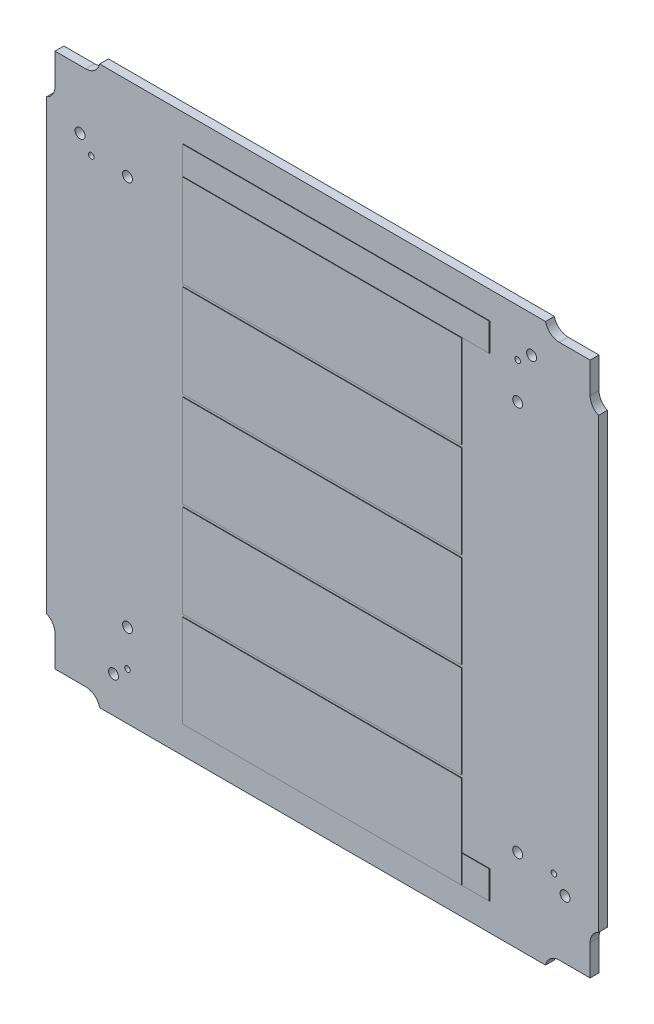
SolidWorks part; units mm, degrees
ref_plane "Front Plane" through (0, 0, 0) normal (0, 0, 1) x (1, 0, 0)
ref_plane "Top Plane" through (0, 0, 0) normal (0, 1, 0) x (1, 0, 0)
ref_plane "Right Plane" through (0, 0, 0) normal (1, 0, 0) x (0, 0, -1)
ref_plane "Plane1" through (0, 0, 1.5875) normal (0, 0, 1) x (1, 0, 0)
sketch "Sketch1" plane through (0, 0, 1.5875) normal (0, 0, 1) x (1, 0, 0)
  line L0 (49.5, 50) -> (-49.5, 50)
  line L1 (-49.5, 50) -> (-49.5, -50)
  line L2 (-49.5, -50) -> (49.5, -50)
  line L3 (49.5, -50) -> (49.5, 50)
  dimension "D1" = 99
  dimension "D2" = 100
extrude "Boss-Extrude1" add sketch "Sketch1" against normal blind 1.5875
sketch "Sketch2" plane through (0, 0, 0) normal (0, 0, -1) x (-1, 0, 0)
  line L0 (48, -42.4819) -> (48, -50)
  line L1 (48, -50) -> (49.5, -50)
  line L2 (49.5, -50) -> (49.5, -40.1646)
  line L3 (-49.5, -50) -> (-49.5, 50) construction
  line L4 (49.5, -50) -> (-49.5, -50) construction
  arc A0 (49.5, -40.1646) -> (48, -42.4819) centre (50.54, -42.4819) ccw
  dimension "D1" = 2.54
  dimension "D2" = 97.5
  dimension "D3" = 99
  dimension "D4" = 7.5181
extrude "Cut-Extrude1" cut sketch "Sketch2" against normal through all
sketch "Sketch3" plane through (0, 0, 0) normal (0, 0, -1) x (-1, 0, 0)
  line L0 (48, -48) -> (42.4819, -48)
  line L1 (40, -50) -> (48, -50)
  line L2 (48, -50) -> (48, -48)
  line L3 (49.5, 50) -> (49.5, -40.1646) construction
  arc A0 (42.4819, -48) -> (40, -50) centre (42.4819, -50.54) ccw
  dimension "D1" = 2.54
  dimension "D2" = 1.5
  dimension "D3" = 7.0181
  dimension "D4" = 9.5
extrude "Cut-Extrude2" cut sketch "Sketch3" against normal through all
sketch "Sketch4" plane through (0, 0, 0) normal (0, 0, -1) x (-1, 0, 0)
  line L0 (-42.4819, -48) -> (-49.5, -48)
  line L1 (-49.5, -48) -> (-49.5, -50)
  line L2 (-49.5, -50) -> (-40, -50)
  line L3 (48, -42.4819) -> (48, -48) construction
  line L4 (40, -50) -> (-49.5, -50) construction
  arc A0 (-40, -50) -> (-42.4819, -48) centre (-42.4819, -50.54) ccw
  dimension "D1" = 2.54
  dimension "D2" = 88
  dimension "D3" = 90.4819
  dimension "D4" = 97.5
  dimension "D5" = 2
extrude "Cut-Extrude3" cut sketch "Sketch4" against normal through all
sketch "Sketch5" plane through (0, 0, 0) normal (0, 0, -1) x (-1, 0, 0)
  line L0 (-48, -48) -> (-48, -42.4819)
  line L1 (-49.5, -40.1646) -> (-49.5, -48)
  line L2 (-49.5, -48) -> (-48, -48)
  line L3 (40, -50) -> (-40, -50) construction
  arc A0 (-48, -42.4819) -> (-49.5, -40.1646) centre (-50.54, -42.4819) ccw
  dimension "D1" = 2.54
  dimension "D2" = 96
  dimension "D3" = 97.5
  dimension "D4" = 2
  dimension "D5" = 7.5181
extrude "Cut-Extrude4" cut sketch "Sketch5" against normal through all
sketch "Sketch6" plane through (0, 0, 0) normal (0, 0, -1) x (-1, 0, 0)
  line L0 (-48, 42.4819) -> (-48, 50)
  line L1 (-48, 50) -> (-49.5, 50)
  line L2 (-49.5, 50) -> (-49.5, 40.1646)
  line L3 (-49.5, -40.1646) -> (-49.5, 50) construction
  line L4 (40, -50) -> (-40, -50) construction
  arc A0 (-49.5, 40.1646) -> (-48, 42.4819) centre (-50.54, 42.4819) ccw
  dimension "D1" = 2.54
  dimension "D2" = 1.5
  dimension "D3" = 90.1646
  dimension "D4" = 92.4819
  dimension "D5" = 100
extrude "Cut-Extrude5" cut sketch "Sketch6" against normal through all
sketch "Sketch7" plane through (0, 0, 0) normal (0, 0, -1) x (-1, 0, 0)
  line L0 (-48, 48) -> (-42.4819, 48)
  line L1 (-40, 50) -> (-48, 50)
  line L2 (-48, 50) -> (-48, 48)
  line L3 (-49.5, -40.1646) -> (-49.5, 40.1646) construction
  line L4 (-42.4819, -48) -> (-48, -48) construction
  arc A0 (-42.4819, 48) -> (-40, 50) centre (-42.4819, 50.54) ccw
  dimension "D1" = 2.54
  dimension "D2" = 1.5
  dimension "D3" = 7.0181
  dimension "D4" = 9.5
  dimension "D5" = 96
extrude "Cut-Extrude6" cut sketch "Sketch7" against normal through all
sketch "Sketch8" plane through (0, 0, 0) normal (0, 0, -1) x (-1, 0, 0)
  line L0 (42.4819, 48) -> (49.5, 48)
  line L1 (49.5, 48) -> (49.5, 50)
  line L2 (49.5, 50) -> (40, 50)
  line L3 (-49.5, -40.1646) -> (-49.5, 40.1646) construction
  line L4 (-40, 50) -> (49.5, 50) construction
  arc A0 (40, 50) -> (42.4819, 48) centre (42.4819, 50.54) ccw
  dimension "D1" = 2.54
  dimension "D2" = 89.5
  dimension "D3" = 91.9819
  dimension "D4" = 99
  dimension "D5" = 0.54
extrude "Cut-Extrude7" cut sketch "Sketch8" against normal through all
sketch "Sketch9" plane through (0, 0, 0) normal (0, 0, -1) x (-1, 0, 0)
  line L0 (48, 48) -> (48, 42.4819)
  line L1 (49.5, 40.1646) -> (49.5, 48)
  line L2 (49.5, 48) -> (48, 48)
  line L3 (-49.5, -40.1646) -> (-49.5, 40.1646) construction
  line L4 (-40, 50) -> (40, 50) construction
  arc A0 (48, 42.4819) -> (49.5, 40.1646) centre (50.54, 42.4819) ccw
  dimension "D1" = 2.54
  dimension "D2" = 97.5
  dimension "D3" = 99
  dimension "D4" = 2
  dimension "D5" = 7.5181
extrude "Cut-Extrude8" cut sketch "Sketch9" against normal through all
sketch "Sketch10" plane through (0, 0, 1.5875) normal (0, 0, 1) x (1, 0, 0)
  line L0 (25, 23.4) -> (-25, 23.4)
  line L1 (-25, 23.4) -> (-25, 40)
  line L2 (-25, 40) -> (25, 40)
  line L3 (25, 40) -> (25, 23.4)
  line L4 (-49.5, 40.1646) -> (-49.5, -40.1646) construction
  line L5 (-40, -50) -> (40, -50) construction
  dimension "D1" = 24.5
  dimension "D2" = 74.5
  dimension "D3" = 73.4
  dimension "D4" = 90
extrude "Boss-Extrude2" add sketch "Sketch10" along normal blind 0.1
sketch "Sketch11" plane through (0, 0, 1.5875) normal (0, 0, 1) x (1, 0, 0)
  line L0 (25, 6.3) -> (-25, 6.3)
  line L1 (-25, 6.3) -> (-25, 22.9)
  line L2 (-25, 22.9) -> (25, 22.9)
  line L3 (25, 22.9) -> (25, 6.3)
  line L4 (-49.5, 40.1646) -> (-49.5, -40.1646) construction
  line L5 (-40, -50) -> (40, -50) construction
  dimension "D1" = 24.5
  dimension "D2" = 74.5
  dimension "D3" = 56.3
  dimension "D4" = 72.9
extrude "Boss-Extrude3" add sketch "Sketch11" along normal blind 0.1
sketch "Sketch12" plane through (0, 0, 1.5875) normal (0, 0, 1) x (1, 0, 0)
  line L0 (25, -10.8) -> (-25, -10.8)
  line L1 (-25, -10.8) -> (-25, 5.8)
  line L2 (-25, 5.8) -> (25, 5.8)
  line L3 (25, 5.8) -> (25, -10.8)
  line L4 (-49.5, 40.1646) -> (-49.5, -40.1646) construction
  line L5 (-40, -50) -> (40, -50) construction
  dimension "D1" = 24.5
  dimension "D2" = 74.5
  dimension "D3" = 39.2
  dimension "D4" = 55.8
extrude "Boss-Extrude4" add sketch "Sketch12" along normal blind 0.1
sketch "Sketch13" plane through (0, 0, 1.5875) normal (0, 0, 1) x (1, 0, 0)
  line L0 (25, -27.9) -> (-25, -27.9)
  line L1 (-25, -27.9) -> (-25, -11.3)
  line L2 (-25, -11.3) -> (25, -11.3)
  line L3 (25, -11.3) -> (25, -27.9)
  line L4 (-49.5, 40.1646) -> (-49.5, -40.1646) construction
  line L5 (-40, -50) -> (40, -50) construction
  dimension "D1" = 24.5
  dimension "D2" = 74.5
  dimension "D3" = 22.1
  dimension "D4" = 38.7
extrude "Boss-Extrude5" add sketch "Sketch13" along normal blind 0.1
sketch "Sketch14" plane through (0, 0, 1.5875) normal (0, 0, 1) x (1, 0, 0)
  line L0 (25, -45) -> (-25, -45)
  line L1 (-25, -45) -> (-25, -28.4)
  line L2 (-25, -28.4) -> (25, -28.4)
  line L3 (25, -28.4) -> (25, -45)
  line L4 (-49.5, 40.1646) -> (-49.5, -40.1646) construction
  line L5 (-40, -50) -> (40, -50) construction
  dimension "D1" = 24.5
  dimension "D2" = 74.5
  dimension "D3" = 5
  dimension "D4" = 21.6
extrude "Boss-Extrude6" add sketch "Sketch14" along normal blind 0.1
sketch "Sketch15" plane through (0, 0, 1.5875) normal (0, 0, 1) x (1, 0, 0)
  line L0 (-25, 40.1) -> (-25, 45.1)
  line L1 (-25, 45.1) -> (30, 45.1)
  line L2 (30, 45.1) -> (30, 40.1)
  line L3 (30, 40.1) -> (-25, 40.1)
  line L4 (-49.5, 40.1646) -> (-49.5, -40.1646) construction
  line L5 (-40, -50) -> (40, -50) construction
  dimension "D1" = 24.5
  dimension "D2" = 79.5
  dimension "D3" = 90.1
  dimension "D4" = 95.1
extrude "Boss-Extrude7" add sketch "Sketch15" along normal blind 0.1
sketch "Sketch16" plane through (0, 0, 1.5875) normal (0, 0, 1) x (1, 0, 0)
  line L0 (25.1, -45) -> (25.1, -40)
  line L1 (25.1, -40) -> (30, -40)
  line L2 (30, -40) -> (30, -45)
  line L3 (30, -45) -> (25.1, -45)
  line L4 (-49.5, 40.1646) -> (-49.5, -40.1646) construction
  line L5 (-40, -50) -> (40, -50) construction
  dimension "D1" = 74.6
  dimension "D2" = 79.5
  dimension "D3" = 5
  dimension "D4" = 10
extrude "Boss-Extrude8" add sketch "Sketch16" along normal blind 0.1
hole_wizard "#000 Clearance Hole1" positions "Sketch18" profile "Sketch17" hole size "#000" standard "ANSI Inch"
sketch "Sketch18" plane through (0, 0, 1.5875) normal (0, 0, 1) x (1, 0, 0)
  point P0 (41.5, -35)
sketch "Sketch17" plane through (41.5, -35, 1.5875) normal (1, 0, 0) x (0, -1, 0)
  line L0 (0, 0) -> (0, 1.5875)
  line L1 (0, 1.5875) -> (0.5, 1.5875)
  line L2 (0.5, 1.5875) -> (0.5, 0)
  line L5 (0.5, 0) -> (0, 0)
  line L11 (0, -6.35) -> (0, 107.95) construction
  dimension "Thru Hole Dia." = 1
  dimension "Thru Hole Depth" = 1.5875
hole_wizard "#000 Clearance Hole2" positions "Sketch20" profile "Sketch19" hole size "#000" standard "ANSI Inch"
sketch "Sketch20" plane through (0, 0, 0) normal (0, 0, -1) x (-1, 0, 0)
  point P0 (-35, 41.5)
  point P1 (35, -41.5)
  point P2 (41.5, 35)
sketch "Sketch19" plane through (35, 41.5, 0) normal (1, 0, 0) x (0, 1, 0)
  line L0 (0, 0) -> (0, 1.6875)
  line L1 (0, 1.6875) -> (0.5, 1.6875)
  line L2 (0.5, 1.6875) -> (0.5, 0)
  line L5 (0.5, 0) -> (0, 0)
  line L11 (0, -6.35) -> (0, 107.95) construction
  dimension "Thru Hole Dia." = 1
  dimension "Thru Hole Depth" = 1.6875
hole_wizard "#50 (0.07) Diameter Hole1" positions "Sketch22" profile "Sketch21" hole size "#50" standard "ANSI Inch"
sketch "Sketch22" plane through (0, 0, 0) normal (0, 0, -1) x (-1, 0, 0)
  point P0 (-35, 35)
  point P1 (-43.5, -37.5)
  point P2 (-35, -35)
  point P3 (37.5, -43.5)
  point P4 (35, -35)
  point P5 (43.5, 37.5)
  point P6 (35, 35)
sketch "Sketch21" plane through (35, 35, 0) normal (1, 0, 0) x (0, 1, 0)
  line L0 (0, 0) -> (0, 1.6875)
  line L1 (0, 1.6875) -> (0.889, 1.6875)
  line L2 (0.889, 1.6875) -> (0.889, 0)
  line L5 (0.889, 0) -> (0, 0)
  line L11 (0, -6.35) -> (0, 107.95) construction
  dimension "Thru Hole Dia." = 1.778
  dimension "Thru Hole Depth" = 1.6875
hole_wizard "#50 (0.07) Diameter Hole2" positions "Sketch24" profile "Sketch23" hole size "#50" standard "ANSI Inch"
sketch "Sketch24" plane through (0, 0, 1.5875) normal (0, 0, 1) x (1, 0, 0)
  point P0 (37.5, 43.5)
sketch "Sketch23" plane through (37.5, 43.5, 1.5875) normal (1, 0, 0) x (0, -1, 0)
  line L0 (0, 0) -> (0, 1.5875)
  line L1 (0, 1.5875) -> (0.889, 1.5875)
  line L2 (0.889, 1.5875) -> (0.889, 0)
  line L5 (0.889, 0) -> (0, 0)
  line L11 (0, -6.35) -> (0, 107.95) construction
  dimension "Thru Hole Dia." = 1.778
  dimension "Thru Hole Depth" = 1.5875
